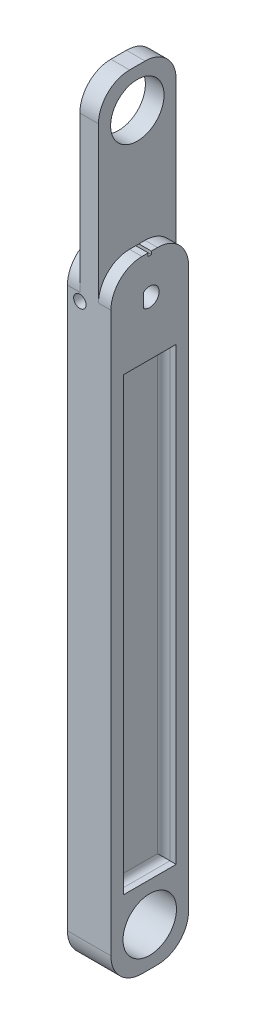
SolidWorks part; units mm, degrees
ref_plane "Alzado" through (0, 0, 0) normal (0, 0, 1) x (1, 0, 0)
ref_plane "Planta" through (0, 0, 0) normal (0, 1, 0) x (1, 0, 0)
ref_plane "Vista lateral" through (0, 0, 0) normal (1, 0, 0) x (0, 0, -1)
sketch "Croquis1" plane through (0, 0, 0) normal (0, 1, 0) x (1, 0, 0)
  line L1 (0, 0) -> (14, 0)
  line L2 (0, 0) -> (0, 25)
  line L3 (0, 25) -> (14, 25)
  line L4 (14, 0) -> (14, 25)
  dimension "D1" = 14
  dimension "D2" = 25
extrude "Saliente-Extruir1" add sketch "Croquis1" along normal blind 200
fillet "Redondeo1" radius 10 1 edges at (7, 0, -25)
fillet "Redondeo2" radius 10 1 edges at (7, 0, 0)
sketch "Croquis2" plane through (14, 0, 0) normal (1, 0, 0) x (0, 0, -1)
  line L0 (0, 200) -> (25, 200) construction
  line L1 (25, 200) -> (25, 10) construction
  line L2 (10.5, 185.2639) -> (10.5, 189.7361)
  arc A0 (10.5, 185.2639) -> (10.5, 189.7361) centre (12.5, 187.5) ccw
  circle A1 centre (12.5, 12.5) radius 8.6
  dimension "D2" = 6
  dimension "D5" = 17.2
  dimension "D1" = 12.5
  dimension "D3" = 12.5
  dimension "D4" = 175
  dimension "D6" = 12.5
  dimension "D7" = 2
extrude "Cortar-Extruir1" cut sketch "Croquis2" against normal blind 28
sketch "Croquis14" plane through (14, 0, 0) normal (1, 0, 0) x (0, 0, -1)
  line L0 (10.5, 185.2639) -> (10.5, 189.7361)
  circle A0 centre (12.5, 187.5) radius 9.913
  arc A1 (10.5, 185.2639) -> (10.5, 189.7361) centre (12.5, 187.5) ccw
  dimension "D1" = 6
  dimension "D2" = 2
extrude "Saliente-Extruir2" add sketch "Croquis14" against normal up to surface (14 mm away) up to face at (0, 187.5, -13)
sketch "Croquis12" plane through (0, 0, -25) normal (0, 0, -1) x (-1, 0, 0)
  line L1 (-14, 200) -> (0, 200) construction
  line L2 (0, 200) -> (0, 10) construction
  circle A0 centre (-4, 187.5) radius 2
  dimension "D1" = 4
  dimension "D2" = 4
  dimension "D3" = 12.5
extrude "Cortar-Extruir7" cut sketch "Croquis12" against normal through all
sketch "Croquis15" plane through (0, 0, 0) normal (-1, 0, 0) x (0, 0, 1)
  line L1 (-8.0822, 190.3) -> (-5.0822, 190.3)
  line L2 (-8.0822, 190.3) -> (-8.0822, 184.7)
  line L3 (-8.0822, 184.7) -> (-5.0822, 184.7)
  line L4 (-5.0822, 190.3) -> (-5.0822, 184.7)
  dimension "D1" = 5.6
  dimension "D2" = 3
extrude "Cortar-Extruir9" cut sketch "Croquis15" against normal blind 8
sketch "Croquis16" plane through (0, 0, 0) normal (-1, 0, 0) x (0, 0, 1)
  line L0 (0, 200) -> (0, 10) construction
  line L1 (-21, 170) -> (-4, 170)
  line L2 (-21, 170) -> (-21, 25)
  line L3 (-21, 25) -> (-4, 25)
  line L4 (-4, 170) -> (-4, 25)
  line L5 (-25, 200) -> (-25, 10) construction
  line L6 (-25, 200) -> (0, 200) construction
  line L7 (-15, 0) -> (-10, 0) construction
  dimension "D1" = 4
  dimension "D2" = 4
  dimension "D3" = 30
  dimension "D4" = 25
extrude "Cortar-Extruir10" cut sketch "Croquis16" against normal blind 4
sketch "Croquis17" plane through (14, 0, 0) normal (1, 0, 0) x (0, 0, -1)
  line L0 (10, 0) -> (15, 0) construction
  line L1 (21, 170) -> (4, 170)
  line L2 (21, 170) -> (21, 25)
  line L3 (21, 25) -> (4, 25)
  line L4 (4, 170) -> (4, 25)
  line L5 (0, 200) -> (25, 200) construction
  line L6 (0, 200) -> (0, 10) construction
  line L7 (25, 200) -> (25, 10) construction
  dimension "D1" = 25
  dimension "D2" = 30
  dimension "D3" = 4
  dimension "D4" = 4
extrude "Cortar-Extruir11" cut sketch "Croquis17" against normal blind 4
fillet "Redondeo5" radius 2 4 edges at (4, 97.5, -21) (4, 170, -12.5) (4, 97.5, -4) (4, 25, -12.5)
fillet "Redondeo6" radius 2 4 edges at (10, 25, -12.5) (10, 97.5, -4) (10, 170, -12.5) (10, 97.5, -21)
sketch "Croquis18" plane through (14, 0, 0) normal (1, 0, 0) x (0, 0, -1)
  line L0 (0, 200) -> (25, 200) construction
  line L1 (12, 200) -> (13, 200)
  line L2 (12, 200) -> (12, 199)
  line L3 (12, 199) -> (13, 199)
  line L4 (13, 200) -> (13, 199)
  point P6 (12.5, 187.5)
  point P7 (12.5, 199)
  dimension "D1" = 1
  dimension "D2" = 1
extrude "Cortar-Extruir12" cut sketch "Croquis18" against normal through all
sketch "Croquis19" plane through (0, 200, 0) normal (0, 1, 0) x (1, 0, 0)
  line L0 (0, 0) -> (14, 0) construction
  line L1 (10, 0) -> (4, 0)
  line L2 (10, 0) -> (10, 25)
  line L3 (10, 25) -> (4, 25)
  line L4 (4, 0) -> (4, 25)
  line L5 (14, 25) -> (0, 25) construction
  point P8 (7, 0)
  point P9 (7, 0)
  dimension "D1" = 6
extrude "Saliente-Extruir3" add sketch "Croquis19" along normal blind 50
sketch "Croquis20" plane through (10, 0, 0) normal (1, 0, 0) x (0, 0, -1)
  line L0 (25, 250) -> (25, 200) construction
  circle A0 centre (12.5, 237.5) radius 8.6
  arc A1 (10.5, 185.2639) -> (10.5, 189.7361) centre (12.5, 187.5) ccw construction
  dimension "D1" = 17.2
  dimension "D2" = 50
  dimension "D3" = 12.5
extrude "Cortar-Extruir13" cut sketch "Croquis20" against normal blind 6
fillet "Redondeo7" radius 10 1 edges at (7, 250, 0)
fillet "Redondeo8" radius 10 1 edges at (7, 250, -25)
fillet "Redondeo9" radius 10 1 edges at (2, 200, 0)
fillet "Redondeo10" radius 10 1 edges at (12, 200, 0)
fillet "Redondeo11" radius 10 1 edges at (12, 200, -25)
fillet "Redondeo12" radius 10 1 edges at (2, 200, -25)
